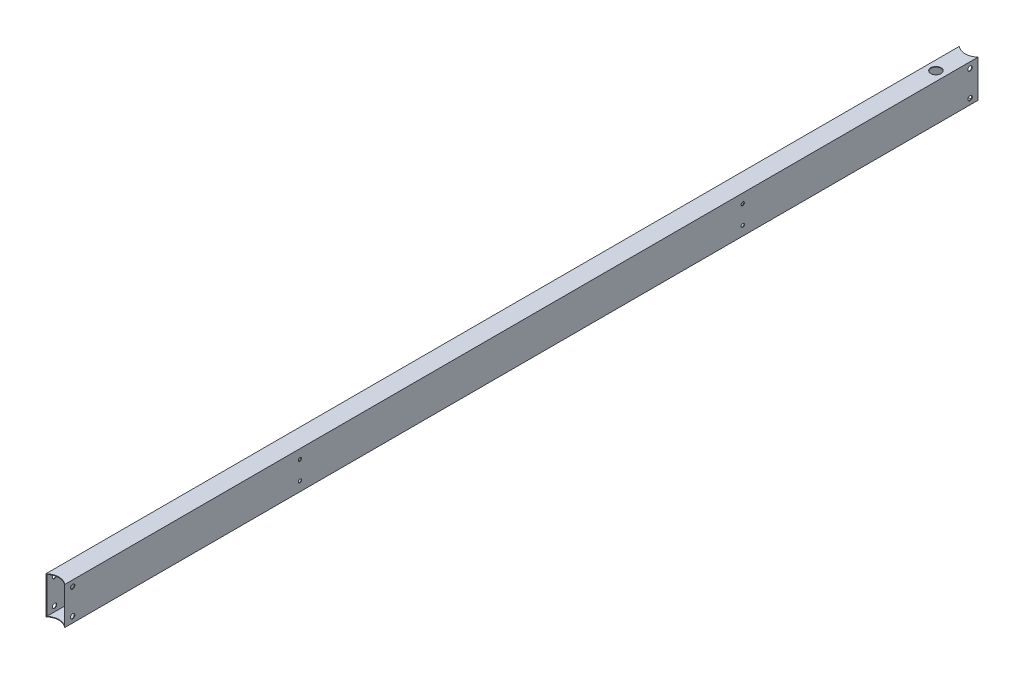
SolidWorks part; units mm, degrees
ref_plane "Front Plane" through (0, 0, 0) normal (0, 0, 1) x (1, 0, 0)
ref_plane "Top Plane" through (0, 0, 0) normal (0, 1, 0) x (1, 0, 0)
ref_plane "Right Plane" through (0, 0, 0) normal (1, 0, 0) x (0, 0, -1)
sketch "Sketch1" plane through (0, 0, 0) normal (0, 0, 1) x (1, 0, 0)
  line L0 (1.2, 78.8) -> (38.8, 78.8)
  line L1 (0, 0) -> (40, 0)
  line L2 (0, 0) -> (0, 80)
  line L3 (0, 80) -> (40, 80)
  line L4 (40, 0) -> (40, 80)
  line L5 (38.8, 1.2) -> (38.8, 78.8)
  line L6 (1.2, 1.2) -> (38.8, 1.2)
  line L7 (1.2, 1.2) -> (1.2, 78.8)
  dimension "D1" = 40
  dimension "D2" = 80
  dimension "D3" = 1.2
extrude "Boss-Extrude1" add sketch "Sketch1" along normal blind 1955
sketch "Sketch2" plane through (0, 80, 0) normal (0, 1, 0) x (1, 0, 0)
  line L0 (0, 0) -> (40, 0)
  line L1 (0, -1955) -> (40, -1955)
  line L2 (20, 0) -> (20, -180.05) construction
  arc A0 (0, 0) -> (40, 0) centre (20, 22.3607) ccw
  arc A1 (0, -1955) -> (40, -1955) centre (20, -1977.3607) cw
  circle A2 centre (20, -70) radius 11
  dimension "D1" = 30
  dimension "D2" = 30
  dimension "D3" = 22
  dimension "D4" = 70
extrude "Cut-Extrude1" cut sketch "Sketch2" against normal blind 1955
sketch "Sketch3" plane through (40, 0, 0) normal (1, 0, 0) x (0, 0, -1)
  line L0 (-977.5, 80) -> (-977.5, 0) construction
  line L1 (-1955, 80) -> (0, 80) construction
  line L2 (-1955, 0) -> (0, 0) construction
  line L3 (0, 0) -> (0, 80) construction
  line L4 (-17, 12.5) -> (-1938, 12.5) construction
  line L5 (-17, 12.5) -> (-17, 67.5) construction
  line L6 (-17, 67.5) -> (-1938, 67.5) construction
  line L7 (-1938, 12.5) -> (-1938, 67.5) construction
  line L8 (-17, 12.5) -> (-1938, 67.5) construction
  line L9 (-17, 67.5) -> (-1938, 12.5) construction
  circle A0 centre (-17, 67.5) radius 4.75
  circle A1 centre (-17, 12.5) radius 4.75
  circle A2 centre (-1938, 67.5) radius 4.75
  circle A3 centre (-1938, 12.5) radius 4.75
  point P6 (-977.5, 40)
  dimension "D3" = 9.5
  dimension "D1" = 55
  dimension "D2" = 17
extrude "Cut-Extrude2" cut sketch "Sketch3" against normal through all
sketch "Sketch4" plane through (40, 0, 0) normal (1, 0, 0) x (0, 0, -1)
  line L0 (-977.5, 80) -> (-977.5, 0) construction
  line L1 (-1955, 80) -> (0, 80) construction
  line L2 (-1955, 0) -> (0, 0) construction
  line L4 (-503.5, 20) -> (-1451.5, 20) construction
  line L5 (-503.5, 20) -> (-503.5, 60) construction
  line L6 (-503.5, 60) -> (-1451.5, 60) construction
  line L7 (-1451.5, 20) -> (-1451.5, 60) construction
  line L8 (-503.5, 20) -> (-1451.5, 60) construction
  line L9 (-503.5, 60) -> (-1451.5, 20) construction
  circle A0 centre (-1451.5, 60) radius 3.5
  circle A1 centre (-1451.5, 20) radius 3.5
  circle A2 centre (-503.5, 60) radius 3.5
  circle A3 centre (-503.5, 20) radius 3.5
  point P6 (-977.5, 40)
  dimension "D3" = 7
  dimension "D1" = 40
  dimension "D2" = 948
extrude "Cut-Extrude3" cut sketch "Sketch4" against normal through all
